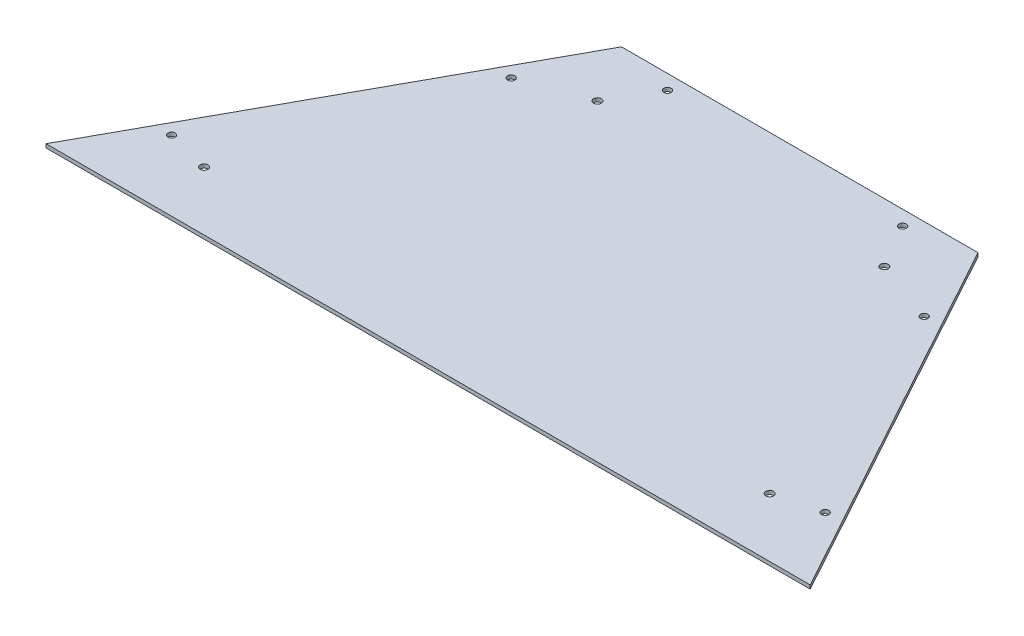
SolidWorks part; units mm, degrees
material "PC High Viscosity"
ref_plane "Front Plane" through (0, 0, 0) normal (0, 0, 1) x (1, 0, 0)
ref_plane "Top Plane" through (0, 0, 0) normal (0, 1, 0) x (1, 0, 0)
ref_plane "Right Plane" through (0, 0, 0) normal (1, 0, 0) x (0, 0, -1)
sketch "Sketch1" plane through (0, 0, 0) normal (0, 1, 0) x (1, 0, 0)
  line L0 (-330.2, 0) -> (-154.051, 321.1289)
  line L1 (-154.051, 321.1289) -> (154.051, 321.1289)
  line L2 (154.051, 321.1289) -> (330.2, 0)
  line L3 (330.2, 0) -> (-330.2, 0)
  point P4 (0, 0)
  dimension "D1" = 660.4
  dimension "D2" = 366.268
  dimension "D3" = 308.102
extrude "Boss-Extrude1" add sketch "Sketch1" along normal blind 3.175
hole_wizard "1/4 (0.25) Diameter Hole1" positions "Sketch2" profile "Sketch3" hole size "1/4" standard "ANSI Inch" end condition through all
sketch "Sketch2" plane through (0, 3.175, 0) normal (0, 1, 0) x (1, 0, 0)
  line L0 (-101.6, 308.4289) -> (-101.6, 321.1289)
  line L1 (154.051, 321.1289) -> (-154.051, 321.1289) construction
  line L3 (-178.4636, 250.2163) -> (-189.5984, 256.3241)
  line L4 (-154.051, 321.1289) -> (-330.2, 0) construction
  line L6 (-282.4183, 60.7013) -> (-293.5532, 66.8091)
  line L8 (0, 0) -> (0, 321.1289) construction
  point P0 (-282.4183, 60.7013)
  point P2 (-178.4636, 250.2163)
  point P4 (-101.6, 308.4289)
  point P28 (282.4183, 60.7013)
  point P29 (178.4636, 250.2163)
  point P30 (101.6, 308.4289)
  dimension "D1" = 12.7
  dimension "D2" = 76.2
  dimension "D3" = 292.354
  dimension "D4" = 101.6
sketch "Sketch3" plane through (-282.4183, 3.175, -60.7013) normal (1, 0, 0) x (0, 0, 1)
  line L0 (0, 0) -> (0, 3.175)
  line L1 (0, 3.175) -> (3.175, 3.175)
  line L2 (3.175, 3.175) -> (3.175, 0)
  line L5 (3.175, 0) -> (0, 0)
  line L11 (0, -6.35) -> (0, 107.95) construction
  dimension "Thru Hole Dia." = 6.35
  dimension "Thru Hole Depth" = 3.175
hole_wizard "1/4 Clearance Hole1" positions "Sketch4" profile "Sketch5" hole size "1/4" standard "ANSI Inch" end condition through all
sketch "Sketch4" plane through (0, 3.175, 0) normal (0, 1, 0) x (1, 0, 0)
  line L0 (0, 0) -> (0, 321.1289) construction
  line L1 (154.051, 321.1289) -> (-154.051, 321.1289) construction
  line L3 (-330.2, 0) -> (330.2, 0) construction
  point P0 (-123.952, 270.256)
  point P2 (-244.348, 50.8)
  point P13 (244.348, 50.8)
  point P14 (123.952, 270.256)
  dimension "D1" = 50.8
  dimension "D2" = 244.348
  dimension "D3" = 123.952
  dimension "D4" = 270.256
sketch "Sketch5" plane through (-123.952, 3.175, -270.256) normal (1, 0, 0) x (0, 0, 1)
  line L0 (0, 0) -> (0, 3.175)
  line L1 (0, 3.175) -> (3.3782, 3.175)
  line L2 (3.3782, 3.175) -> (3.3782, 0)
  line L5 (3.3782, 0) -> (0, 0)
  line L11 (0, -6.35) -> (0, 107.95) construction
  dimension "Thru Hole Dia." = 6.7564
  dimension "Thru Hole Depth" = 3.175
